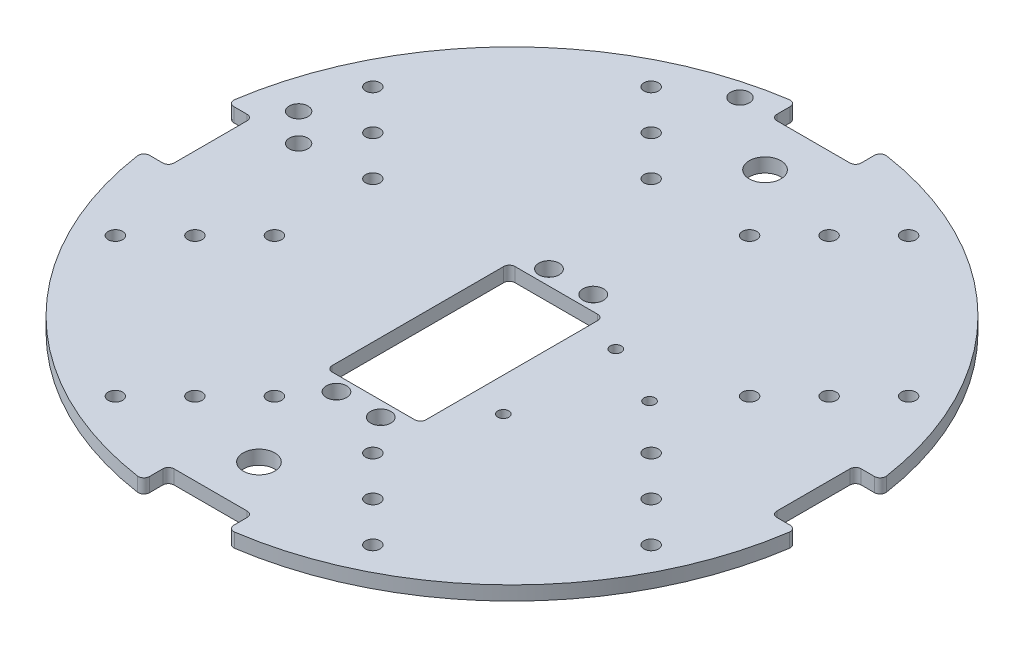
SolidWorks part; units mm, degrees
material "G10"
ref_plane "Front Plane" through (0, 0, 0) normal (0, 0, 1) x (1, 0, 0)
ref_plane "Top Plane" through (0, 0, 0) normal (0, 1, 0) x (1, 0, 0)
ref_plane "Right Plane" through (0, 0, 0) normal (1, 0, 0) x (0, 0, -1)
sketch "Sketch1" plane through (0, 0, 0) normal (0, 1, 0) x (1, 0, 0)
  line L0 (0, 0) -> (0, -95.5682) construction
  line L1 (0, 0) -> (-84.7245, 0) construction
  line L3 (10.6, 10) -> (-10.6, 10)
  line L4 (10.6, 10) -> (10.6, -31.3)
  line L5 (10.6, -31.3) -> (-10.6, -31.3)
  line L6 (-10.6, 10) -> (-10.6, -31.3)
  circle A0 centre (0, 0) radius 74.422
  point P7 (0, 10)
  dimension "D1" = 148.844
  dimension "D4" = 10
  dimension "D5" = 41.3
  dimension "D2" = 21.2
extrude "Boss-Extrude1" add sketch "Sketch1" along normal blind 3.175
hole_wizard "Ø4.6 (4.6) Diameter Hole1" positions "Sketch4" profile "Sketch5" hole size "Ø4.6" standard "ANSI Metric" end condition through all
sketch "Sketch4" plane through (0, 0, 0) normal (0, -1, 0) x (-1, 0, 0)
  line L3 (-10.6, -10.65) -> (10.6, -10.65) construction
  line L4 (-10.6, -31.3) -> (-10.6, 10) construction
  line L5 (10.6, 10) -> (10.6, -31.3) construction
  line L7 (0, 10) -> (0, -31.3) construction
  line L8 (-10.6, 10) -> (10.6, 10) construction
  line L9 (10.6, -31.3) -> (-10.6, -31.3) construction
  point P0 (-5, 13.35)
  point P2 (5, 13.35)
  point P4 (-5, -34.65)
  point P6 (5, -34.65)
  dimension "D1" = 24
  dimension "D2" = 5
  dimension "D3" = 24
  dimension "D4" = 10
sketch "Sketch5" plane through (5, 0, -13.35) normal (1, 0, 0) x (0, 0, -1)
  line L0 (0, 0) -> (0, 3.175)
  line L1 (0, 3.175) -> (2.3, 3.175)
  line L2 (2.3, 3.175) -> (2.3, 0)
  line L5 (2.3, 0) -> (0, 0)
  line L11 (0, -6.35) -> (0, 107.95) construction
  dimension "Thru Hole Dia." = 4.6
  dimension "Thru Hole Depth" = 3.175
hole_wizard "#4 Clearance Hole1" positions "Sketch13" profile "Sketch14" hole size "#4" standard "ANSI Inch" end condition through all
sketch "Sketch13" plane through (0, 0, 0) normal (0, -1, 0) x (-1, 0, 0)
  line L2 (-0.2627, 0.2627) -> (79.1072, -79.1072) construction
  line L3 (-0.9343, 0) -> (106.7607, 0) construction
  line L4 (60.5065, -29.0756) -> (29.0756, -60.5065) construction
  line L7 (24.5855, -56.0163) -> (56.0163, -24.5855) construction
  line L8 (24.5855, -56.0163) -> (33.5657, -64.9966) construction
  line L9 (33.5657, -64.9966) -> (64.9966, -33.5657) construction
  line L10 (56.0163, -24.5855) -> (64.9966, -33.5657) construction
  line L11 (24.5855, -56.0163) -> (64.9966, -33.5657) construction
  line L12 (33.5657, -64.9966) -> (56.0163, -24.5855) construction
  line L13 (0, 0) -> (33.5657, -64.9966) construction
  line L15 (33.5657, -64.9966) -> (34.1484, -66.125) construction
  line L18 (24.5855, -56.0163) -> (11.1151, -42.546) construction
  circle A0 centre (0, 0) radius 74.422 construction
  point P0 (60.5065, -29.0756)
  point P18 (29.0756, -60.5065)
  point P112 (44.791, -44.791)
  point P124 (11.1151, -42.546)
  point P125 (20.0953, -51.5262)
  point P128 (51.5262, -20.0953)
  point P129 (42.546, -11.1151)
  dimension "D3" = 45
  dimension "D1" = 22.225
  dimension "D2" = 12.7
  dimension "D4" = 1.27
  dimension "D5" = 6.35
  dimension "D6" = 19.05
sketch "Sketch14" plane through (-60.5065, 0, 29.0756) normal (1, 0, 0) x (0, 0, -1)
  line L0 (0, 0) -> (0, 3.175)
  line L1 (0, 3.175) -> (1.6319, 3.175)
  line L2 (1.6319, 3.175) -> (1.6319, 0)
  line L5 (1.6319, 0) -> (0, 0)
  line L11 (0, -6.35) -> (0, 107.95) construction
  dimension "Thru Hole Dia." = 3.2639
  dimension "Thru Hole Depth" = 3.175
pattern_circular "CirPattern2" count 4 over 360 about axis through (0, 0, 0) along (0, 1, 0) of "#4 Clearance Hole1"
hole_wizard "1/4 Clearance Hole1" positions "Sketch15" profile "Sketch16" hole size "1/4" standard "ANSI Inch" end condition through all
sketch "Sketch15" plane through (0, 3.175, 0) normal (0, 1, 0) x (1, 0, 0)
  line L0 (0, -57.15) -> (0, 57.15) construction
  point P0 (0, 57.15)
  point P2 (0, -57.15)
  dimension "D1" = 114.3
sketch "Sketch16" plane through (0, 3.175, -57.15) normal (1, 0, 0) x (0, 0, 1)
  line L0 (0, 0) -> (0, 3.175)
  line L1 (0, 3.175) -> (3.5712, 3.175)
  line L2 (3.5712, 3.175) -> (3.5712, 0)
  line L5 (3.5712, 0) -> (0, 0)
  line L11 (0, -6.35) -> (0, 107.95) construction
  dimension "Thru Hole Dia." = 7.1425
  dimension "Thru Hole Depth" = 3.175
hole_wizard "#26 (0.147) Diameter Hole1" positions "Sketch17" profile "Sketch18" hole size "#26" standard "ANSI Inch"
sketch "Sketch17" plane through (0, 3.175, 0) normal (0, 1, 0) x (1, 0, 0)
  line L22 (-3.8533, 35.2296) -> (21.6026, 60.6854)
  line L23 (-3.8533, 35.2296) -> (35.7447, -4.3684)
  line L24 (21.6026, 60.6854) -> (61.2006, 21.0874)
  line L25 (35.7447, -4.3684) -> (61.2006, 21.0874)
  line L26 (-19.9329, -61.842) -> (-9.1566, -51.0657)
  line L27 (-19.9329, -61.842) -> (-61.242, -20.5329)
  line L28 (-9.1566, -51.0657) -> (-50.4657, -9.7566)
  line L29 (-61.242, -20.5329) -> (-50.4657, -9.7566)
  line L32 (10.6, -31.3) -> (10.6, 10) construction
  line L35 (-10.6, -31.3) -> (10.6, -31.3) construction
  point P403 (-61.242, -20.5329)
  point P406 (-50.4657, -9.7566)
  point P409 (-9.1566, -51.0657)
  point P412 (-19.9329, -61.842)
  point P415 (35.7447, -4.3684)
  point P418 (61.2006, 21.0874)
  point P421 (21.6026, 60.6854)
  point P424 (-3.8533, 35.2296)
  dimension "D5" = 27.94
  dimension "D1" = 57.15
  dimension "D2" = 29.21
  dimension "D3" = 36
  dimension "D4" = 7.62
  dimension "D6" = 56
  dimension "D7" = 45
  dimension "D8" = 58.42
  dimension "D9" = 15.24
  dimension "D10" = 45
sketch "Sketch18" plane through (-3.8533, 3.175, -35.2296) normal (1, 0, 0) x (0, 0, 1)
  line L0 (0, 0) -> (0, 3.175)
  line L1 (0, 3.175) -> (1.8669, 3.175)
  line L2 (1.8669, 3.175) -> (1.8669, 0)
  line L5 (1.8669, 0) -> (0, 0)
  line L11 (0, -6.35) -> (0, 107.95) construction
  dimension "Thru Hole Dia." = 3.7338
  dimension "Thru Hole Depth" = 3.175
sketch "Sketch19" plane through (0, 0, 0) normal (0, -1, 0) x (1, 0, 0)
  line L0 (0, 0) -> (0, -74.422) construction
  line L2 (-9.525, -68.072) -> (9.525, -68.072)
  line L3 (-9.525, -68.072) -> (-9.525, -80.772)
  line L4 (-9.525, -80.772) -> (9.525, -80.772)
  line L5 (9.525, -68.072) -> (9.525, -80.772)
  line L6 (-9.525, -68.072) -> (9.525, -80.772) construction
  line L7 (-9.525, -80.772) -> (9.525, -68.072) construction
  circle A0 centre (0, 0) radius 74.422 construction
  dimension "D1" = 19.05
  dimension "D2" = 12.7
extrude "Cut-Extrude1" cut sketch "Sketch19" against normal through all
pattern_circular "CirPattern3" count 4 over 360 about axis through (0, 0, 0) along (0, 1, 0) of "Cut-Extrude1"
fillet "Fillet1" radius 1.27 20 edges at (73.8099, 1.5875, 9.525) (68.072, 1.5875, 9.525) (73.8099, 1.5875, -9.525) (68.072, 1.5875, -9.525) (9.525, 1.5875, 73.8099) (-9.525, 1.5875, 73.8099) (-73.8099, 1.5875, -9.525) (-73.8099, 1.5875, 9.525) (-9.525, 1.5875, -68.072) (-9.525, 1.5875, -73.8099) (9.525, 1.5875, -73.8099) (9.525, 1.5875, -68.072) (-68.072, 1.5875, 9.525) (-68.072, 1.5875, -9.525) (10.6, 1.5875, 31.3) (-10.6, 1.5875, 31.3) (-10.6, 1.5875, -10) (10.6, 1.5875, -10) (-9.525, 1.5875, 68.072) (9.525, 1.5875, 68.072)
hole_wizard "#19 (0.166) Diameter Hole1" positions "Sketch22" profile "Sketch21" hole size "#19" standard "ANSI Inch" end condition through all
sketch "Sketch22" plane through (0, 3.175, 0) normal (0, 1, 0) x (1, 0, 0)
  circle A2 centre (-16.9632, 68.4487) radius 1.2192 construction
  circle A3 centre (-64.1096, 15.9142) radius 1.2192 construction
  circle A4 centre (-57.8234, 9.628) radius 1.2192 construction
  point P61 (-16.9632, 68.4487)
  point P67 (-64.1096, 15.9142)
  point P72 (-57.8234, 9.628)
sketch "Sketch21" plane through (-16.9632, 3.175, -68.4487) normal (1, 0, 0) x (0, 0, 1)
  line L0 (0, 0) -> (0, 3.175)
  line L1 (0, 3.175) -> (2.1082, 3.175)
  line L2 (2.1082, 3.175) -> (2.1082, 0)
  line L5 (2.1082, 0) -> (0, 0)
  line L11 (0, -6.35) -> (0, 107.95) construction
  dimension "Thru Hole Dia." = 4.2164
  dimension "Thru Hole Depth" = 3.175
hole_wizard "Tap Drill for M3x0.5 Tap1" positions "Sketch23" profile "Sketch24" hole size "M3x0.5" standard "ANSI Metric"
sketch "Sketch23" plane through (0, 3.175, 0) normal (0, 1, 0) x (1, 0, 0)
  circle A0 centre (18.22, 5.225) radius 1.5 construction
  circle A1 centre (18.22, -20.175) radius 1.5 construction
  point P0 (18.22, 5.225)
  point P3 (18.22, -20.175)
  point P15 (32.19, -1.125)
sketch "Sketch24" plane through (18.22, 3.175, -5.225) normal (1, 0, 0) x (0, 0, 1)
  line L0 (0, 0) -> (0, 4.5611)
  line L1 (0, 4.5611) -> (1.25, 3.81)
  line L2 (1.25, 3.81) -> (1.25, 0)
  line L5 (1.25, 0) -> (0, 0)
  line L10 (0, 4.5611) -> (-1.25, 3.81) construction
  line L11 (0, -6.35) -> (0, 107.95) construction
  dimension "Hole Dia." = 2.5
  dimension "Hole Depth" = 3.81
  dimension "Drill Angle" = 118
equation "\"D4@Sketch1\" = 9.5mm + \"gap\""
equation "\"D5@Sketch1\" = 40.3mm + 2 * \"gap\""
equation "\"D2@Sketch1\"= 20.2mm + 2 * \"gap\""
equation "\"gap\"= 0.5mm"
equation "\"D1@Sketch4\"=24mm"
equation "\"D2@Sketch4\"=5mm"
equation "\"D3@Sketch4\"=24mm"
equation "\"D4@Sketch4\"=10mm"
equation "\"atsFlapWidth\" = 1.5in"
equation "\"D1@Sketch13\"=\"atsFlapWidth\"/2 + 0.125"
